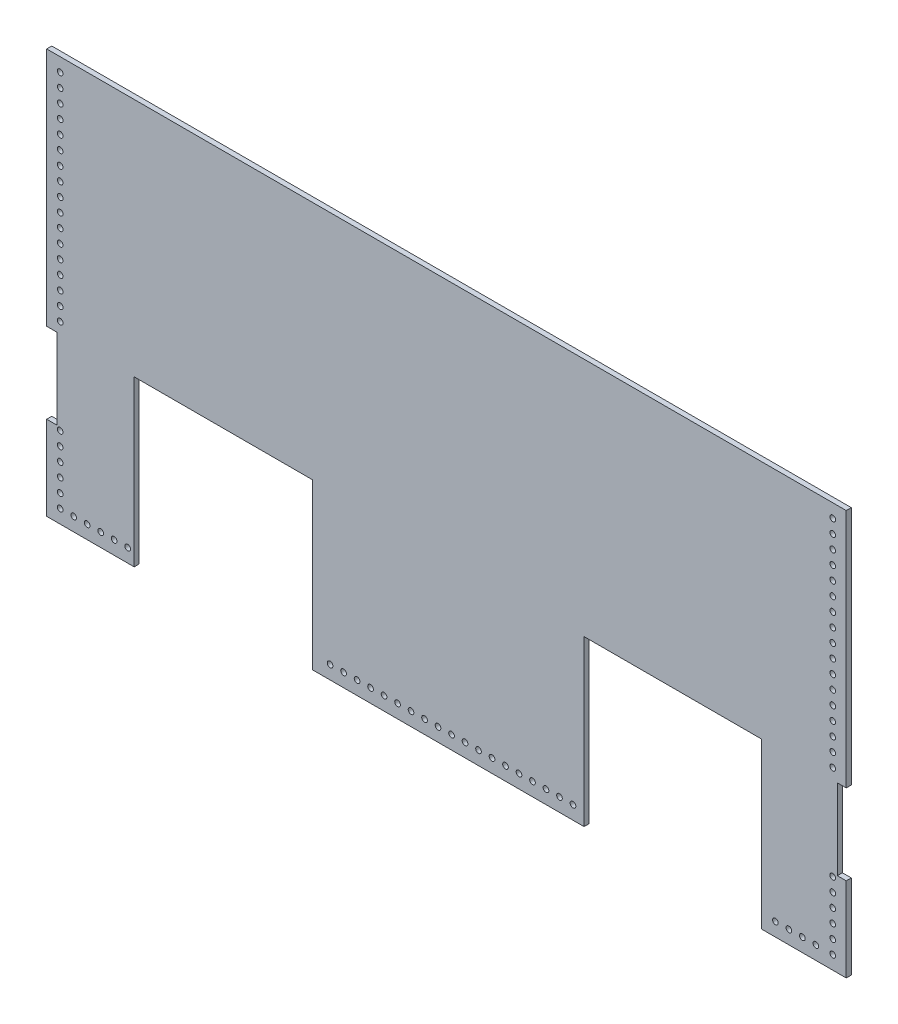
SolidWorks part; units mm, degrees
material "Polypropylene"
ref_plane "Front Plane" through (0, 0, 0) normal (0, 0, 1) x (1, 0, 0)
ref_plane "Top Plane" through (0, 0, 0) normal (0, 1, 0) x (1, 0, 0)
ref_plane "Right Plane" through (0, 0, 0) normal (1, 0, 0) x (0, 0, -1)
sketch "Sketch1" plane through (0, 0, 0) normal (0, 0, 1) x (1, 0, 0)
  line L1 (0, 0) -> (752.475, 0)
  line L2 (0, 0) -> (0, -381)
  line L3 (0, -381) -> (752.475, -381)
  line L4 (752.475, 0) -> (752.475, -381)
  dimension "D1" = 381
  dimension "D2" = 752.475
extrude "Boss-Extrude1" add sketch "Sketch1" along normal blind 4.7625
sketch "Sketch2" plane through (0, 0, 0) normal (0, 0, -1) x (-1, 0, 0)
  line L0 (-752.475, -381) -> (-752.475, 0) construction
  line L1 (-752.475, -301.8032) -> (-744.0955, -301.8032)
  line L2 (-752.475, -301.8032) -> (-752.475, -226.1009)
  line L3 (-752.475, -226.1009) -> (-744.0955, -226.1009)
  line L4 (-744.0955, -301.8032) -> (-744.0955, -226.1009)
  line L5 (-747.0902, -226.1009) -> (-741.9848, -226.1009) construction
extrude "Cut-Extrude1" cut sketch "Sketch2" against normal blind 10.668
sketch "Sketch3" plane through (0, 0, 0) normal (0, 0, -1) x (-1, 0, 0)
  line L0 (-744.0955, -301.8032) -> (4.7625, -299.8134) construction
  line L1 (0, 0) -> (0, -381) construction
  line L2 (0, -301.8032) -> (-9.6827, -301.8032)
  line L3 (0, -301.8032) -> (0, -226.0952)
  line L4 (0, -226.0952) -> (-9.6827, -226.0952)
  line L5 (-9.6827, -301.8032) -> (-9.6827, -226.0952)
extrude "Cut-Extrude2" cut sketch "Sketch3" against normal blind 10.668
sketch "Sketch4" plane through (0, 0, 0) normal (0, 0, -1) x (-1, 0, 0)
  line L0 (-439.7375, -226.1009) -> (-731.8375, -226.1009) construction
  line L1 (-672.6207, -226.1009) -> (-505.7165, -226.1009)
  line L2 (-672.6207, -226.1009) -> (-672.6207, -381)
  line L3 (-672.6207, -381) -> (-505.7165, -381)
  line L4 (-505.7165, -226.1009) -> (-505.7165, -381)
  line L5 (0, -381) -> (-752.475, -381) construction
extrude "Cut-Extrude3" cut sketch "Sketch4" against normal blind 10.668
sketch "Sketch5" plane through (0, 0, 0) normal (0, 0, -1) x (-1, 0, 0)
  line L6 (0, -381) -> (-505.7165, -381) construction
  line L7 (-82.3145, -381) -> (-249.9649, -381)
  line L8 (-82.3145, -381) -> (-82.3145, -226.1009)
  line L9 (-82.3145, -226.1009) -> (-249.9649, -226.1009)
  line L10 (-249.9649, -381) -> (-249.9649, -226.1009)
  line L11 (-20.6375, -226.1009) -> (-312.7375, -226.1009) construction
extrude "Cut-Extrude5" cut sketch "Sketch5" against normal blind 10.668
sketch "Sketch6" plane through (0, 0, 4.7625) normal (0, 0, 1) x (1, 0, 0)
  line L0 (0, -12.7) -> (12.7, -12.7) construction
  line L1 (0, 0) -> (0, -226.0952) construction
  line L2 (12.7, -12.7) -> (12.7, 0) construction
  line L3 (752.475, 0) -> (0, 0) construction
  line L4 (12.7, 0) -> (12.7, -381) construction
  line L5 (0, -381) -> (82.3145, -381) construction
  line L6 (376.2375, 0) -> (376.2375, -381) construction
  line L7 (249.9649, -381) -> (505.7165, -381) construction
  line L8 (739.775, 0) -> (739.775, -381) construction
  line L9 (0, -368.3) -> (752.475, -368.3) construction
  line L10 (0, -301.8032) -> (0, -381) construction
  line L11 (752.475, -381) -> (752.475, -301.8032) construction
  circle A0 centre (12.7, -12.7) radius 2.667
  circle A1 centre (12.7, -25.4) radius 2.667
  circle A2 centre (12.7, -38.1) radius 2.667
  circle A3 centre (12.7, -50.8) radius 2.667
  circle A4 centre (12.7, -63.5) radius 2.667
  circle A5 centre (12.7, -76.2) radius 2.667
  circle A6 centre (12.7, -88.9) radius 2.667
  circle A7 centre (12.7, -101.6) radius 2.667
  circle A8 centre (12.7, -114.3) radius 2.667
  circle A9 centre (12.7, -127) radius 2.667
  circle A10 centre (12.7, -139.7) radius 2.667
  circle A11 centre (12.7, -152.4) radius 2.667
  circle A12 centre (12.7, -165.1) radius 2.667
  circle A13 centre (12.7, -177.8) radius 2.667
  circle A14 centre (12.7, -190.5) radius 2.667
  circle A15 centre (12.7, -203.2) radius 2.667
  circle A16 centre (12.7, -215.9) radius 2.667
  circle A23 centre (12.7, -304.8) radius 2.667
  circle A24 centre (12.7, -317.5) radius 2.667
  circle A25 centre (12.7, -330.2) radius 2.667
  circle A26 centre (12.7, -342.9) radius 2.667
  circle A27 centre (12.7, -355.6) radius 2.667
  circle A28 centre (12.7, -368.3) radius 2.667
  circle A29 centre (739.775, -368.3) radius 2.667
  circle A30 centre (739.775, -355.6) radius 2.667
  circle A31 centre (739.775, -342.9) radius 2.667
  circle A32 centre (739.775, -330.2) radius 2.667
  circle A33 centre (739.775, -304.8) radius 2.667
  circle A34 centre (739.775, -317.5) radius 2.667
  circle A35 centre (739.775, -215.9) radius 2.667
  circle A36 centre (739.775, -203.2) radius 2.667
  circle A37 centre (739.775, -190.5) radius 2.667
  circle A38 centre (739.775, -177.8) radius 2.667
  circle A39 centre (739.775, -165.1) radius 2.667
  circle A40 centre (739.775, -152.4) radius 2.667
  circle A41 centre (739.775, -139.7) radius 2.667
  circle A42 centre (739.775, -127) radius 2.667
  circle A43 centre (739.775, -114.3) radius 2.667
  circle A44 centre (739.775, -101.6) radius 2.667
  circle A45 centre (739.775, -88.9) radius 2.667
  circle A46 centre (739.775, -76.2) radius 2.667
  circle A47 centre (739.775, -63.5) radius 2.667
  circle A48 centre (739.775, -50.8) radius 2.667
  circle A49 centre (739.775, -38.1) radius 2.667
  circle A50 centre (739.775, -25.4) radius 2.667
  circle A51 centre (739.775, -12.7) radius 2.667
  circle A52 centre (25.4, -368.3) radius 2.667
  circle A53 centre (38.1, -368.3) radius 2.667
  circle A54 centre (50.8, -368.3) radius 2.667
  circle A55 centre (63.5, -368.3) radius 2.667
  circle A56 centre (76.2, -368.3) radius 2.667
  circle A57 centre (88.9, -368.3) radius 2.667
  circle A58 centre (101.6, -368.3) radius 2.667
  circle A59 centre (114.3, -368.3) radius 2.667
  circle A60 centre (127, -368.3) radius 2.667
  circle A61 centre (139.7, -368.3) radius 2.667
  circle A62 centre (152.4, -368.3) radius 2.667
  circle A63 centre (165.1, -368.3) radius 2.667
  circle A64 centre (177.8, -368.3) radius 2.667
  circle A65 centre (190.5, -368.3) radius 2.667
  circle A66 centre (203.2, -368.3) radius 2.667
  circle A67 centre (215.9, -368.3) radius 2.667
  circle A68 centre (228.6, -368.3) radius 2.667
  circle A69 centre (241.3, -368.3) radius 2.667
  circle A71 centre (266.7, -368.3) radius 2.667
  circle A72 centre (279.4, -368.3) radius 2.667
  circle A73 centre (292.1, -368.3) radius 2.667
  circle A74 centre (304.8, -368.3) radius 2.667
  circle A75 centre (317.5, -368.3) radius 2.667
  circle A76 centre (330.2, -368.3) radius 2.667
  circle A77 centre (342.9, -368.3) radius 2.667
  circle A78 centre (355.6, -368.3) radius 2.667
  circle A79 centre (368.3, -368.3) radius 2.667
  circle A80 centre (381, -368.3) radius 2.667
  circle A81 centre (393.7, -368.3) radius 2.667
  circle A82 centre (406.4, -368.3) radius 2.667
  circle A83 centre (419.1, -368.3) radius 2.667
  circle A84 centre (431.8, -368.3) radius 2.667
  circle A85 centre (444.5, -368.3) radius 2.667
  circle A86 centre (457.2, -368.3) radius 2.667
  circle A87 centre (469.9, -368.3) radius 2.667
  circle A88 centre (482.6, -368.3) radius 2.667
  circle A89 centre (495.3, -368.3) radius 2.667
  circle A91 centre (520.7, -368.3) radius 2.667
  circle A92 centre (533.4, -368.3) radius 2.667
  circle A93 centre (546.1, -368.3) radius 2.667
  circle A94 centre (558.8, -368.3) radius 2.667
  circle A95 centre (571.5, -368.3) radius 2.667
  circle A96 centre (584.2, -368.3) radius 2.667
  circle A97 centre (596.9, -368.3) radius 2.667
  circle A98 centre (609.6, -368.3) radius 2.667
  circle A99 centre (622.3, -368.3) radius 2.667
  circle A100 centre (635, -368.3) radius 2.667
  circle A101 centre (647.7, -368.3) radius 2.667
  circle A102 centre (660.4, -368.3) radius 2.667
  circle A104 centre (685.8, -368.3) radius 2.667
  circle A105 centre (698.5, -368.3) radius 2.667
  circle A106 centre (711.2, -368.3) radius 2.667
  circle A107 centre (723.9, -368.3) radius 2.667
  circle A108 centre (508, -368.3) radius 2.667 [skipped]
  circle A109 centre (673.1, -368.3) radius 2.667 [skipped]
  circle A110 centre (254, -368.3) radius 2.667 [skipped]
  dimension "D3" = 5.334
  dimension "D1" = 12.7
  dimension "D2" = 12.7
  dimension "D4" = 57
extrude "Cut-Extrude6" cut sketch "Sketch6" against normal through all
